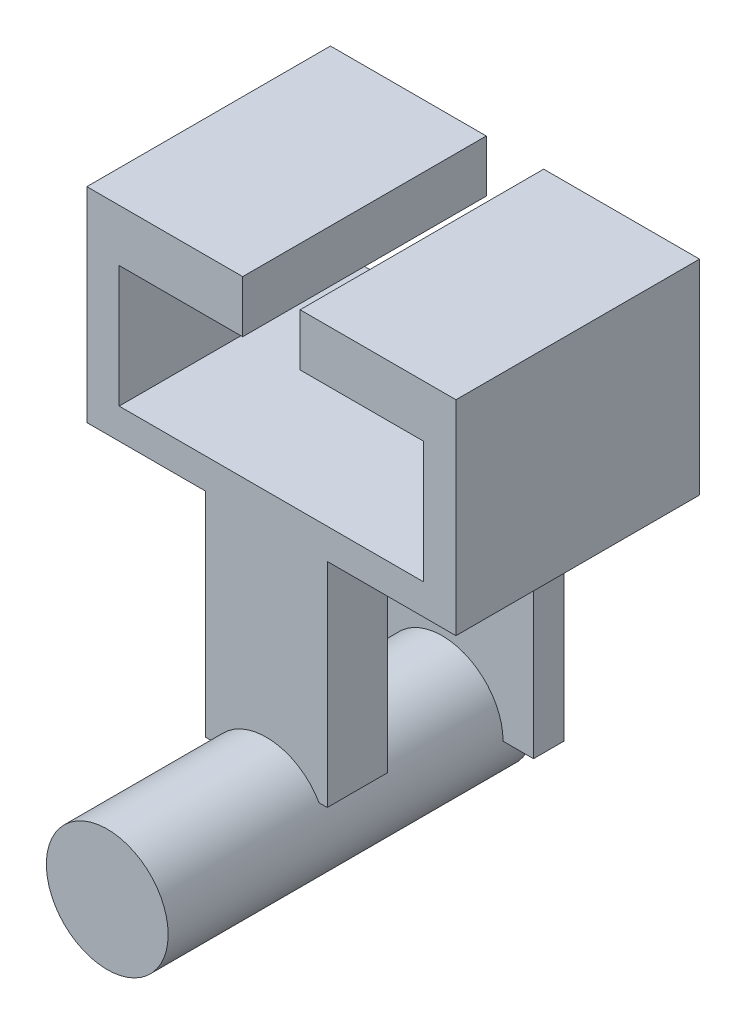
SolidWorks part; units mm, degrees
material "ASTM A36 Steel"
ref_plane "Front Plane" through (0, 0, 0) normal (0, 0, 1) x (1, 0, 0)
ref_plane "Top Plane" through (0, 0, 0) normal (0, 1, 0) x (1, 0, 0)
ref_plane "Right Plane" through (0, 0, 0) normal (1, 0, 0) x (0, 0, -1)
sketch "Sketch3" plane through (0, 0, 0) normal (0, 0, 1) x (1, 0, 0)
  circle A0 centre (0, 0) radius 12.7
  dimension "D1" = 25.4
extrude "Boss-Extrude1" add sketch "Sketch3" along normal blind 76.2
sketch "Sketch4" plane through (0, 0, 0) normal (0, 0, -1) x (-1, 0, 0)
  line L0 (0, 0) -> (19.05, 0)
  line L5 (19.05, 0) -> (19.05, 50.8)
  line L6 (19.05, 50.8) -> (-19.05, 50.8)
  line L7 (-19.05, 50.8) -> (-19.05, 0)
  line L8 (-19.05, 0) -> (0, 0)
  dimension "D1" = 50.8
  dimension "D2" = 38.1
extrude "Boss-Extrude2" add sketch "Sketch4" against normal blind 6.35 contours L7 L8 L0 L5 L6
sketch "Sketch6" plane through (0, 50.8, 0) normal (0, 1, 0) x (1, 0, 0)
  line L1 (-30.7019, 7.7865) -> (32.7981, 7.7865)
  line L2 (-30.7019, 7.7865) -> (-30.7019, -43.0135)
  line L3 (-30.7019, -43.0135) -> (32.7981, -43.0135)
  line L4 (32.7981, 7.7865) -> (32.7981, -43.0135)
  dimension "D1" = 63.5
  dimension "D2" = 50.8
extrude "Boss-Extrude3" add sketch "Sketch6" along normal blind 6.35
sketch "Sketch8" plane through (32.7981, 0, 0) normal (1, 0, 0) x (0, 0, -1)
  line L1 (-43.0135, 57.15) -> (7.7865, 57.15)
  line L2 (-43.0135, 57.15) -> (-43.0135, 50.8)
  line L3 (-43.0135, 50.8) -> (7.7865, 50.8)
  line L4 (7.7865, 57.15) -> (7.7865, 50.8)
sketch "Sketch9" plane through (32.7981, 0, 0) normal (1, 0, 0) x (0, 0, -1)
  line L1 (-43.0135, 57.15) -> (7.7865, 57.15)
  line L2 (-43.0135, 57.15) -> (-43.0135, 50.8)
  line L3 (-43.0135, 50.8) -> (7.7865, 50.8)
  line L4 (7.7865, 57.15) -> (7.7865, 50.8)
extrude "Boss-Extrude4" add sketch "Sketch9" along normal blind 0.3886
sketch "Sketch10" plane through (0, 57.15, 0) normal (0, 1, 0) x (1, 0, 0)
  line L0 (32.7981, -43.0135) -> (32.7981, 7.7865) construction
  line L1 (32.7981, 7.7865) -> (33.1867, 7.7865)
  line L2 (32.7981, 7.7865) -> (32.7981, -43.0135)
  line L3 (32.7981, -43.0135) -> (33.1867, -43.0135)
  line L4 (33.1867, 7.7865) -> (33.1867, -43.0135)
  line L5 (33.1867, 7.7865) -> (-30.7019, 7.7865) construction
extrude "Boss-Extrude5" add sketch "Sketch10" along normal blind 25.4
sketch "Sketch11" plane through (-30.7019, 0, 0) normal (-1, 0, 0) x (0, 0, 1)
  line L1 (-7.7865, 57.15) -> (43.0135, 57.15)
  line L2 (-7.7865, 57.15) -> (-7.7865, 50.8)
  line L3 (-7.7865, 50.8) -> (43.0135, 50.8)
  line L4 (43.0135, 57.15) -> (43.0135, 50.8)
extrude "Boss-Extrude6" add sketch "Sketch11" along normal blind 0.3886
sketch "Sketch13" plane through (0, 57.15, 0) normal (0, 1, 0) x (1, 0, 0)
  line L0 (-31.0906, -43.0135) -> (32.7981, -43.0135) construction
  line L1 (-31.0906, 7.7865) -> (-30.7019, 7.7865)
  line L2 (-31.0906, 7.7865) -> (-31.0906, -43.0135)
  line L3 (-31.0906, -43.0135) -> (-30.7019, -43.0135)
  line L4 (-30.7019, 7.7865) -> (-30.7019, -43.0135)
  dimension "D1" = 0.3886
extrude "Boss-Extrude7" add sketch "Sketch13" along normal blind 25.4
sketch "Sketch14" plane through (0, 82.55, 0) normal (0, 1, 0) x (1, 0, 0)
  line L1 (-31.0906, 7.7865) -> (-30.7019, 7.7865)
  line L2 (-31.0906, 7.7865) -> (-31.0906, -43.0135)
  line L3 (-31.0906, -43.0135) -> (-30.7019, -43.0135)
  line L4 (-30.7019, 7.7865) -> (-30.7019, -43.0135)
extrude "Boss-Extrude8" add sketch "Sketch14" along normal blind 10.8712
sketch "Sketch15" plane through (-30.7019, 0, 0) normal (1, 0, 0) x (0, 0, -1)
  line L0 (7.7865, 93.4212) -> (7.7865, 57.15) construction
  line L1 (-43.0135, 93.4212) -> (7.7865, 93.4212)
  line L2 (-43.0135, 93.4212) -> (-43.0135, 82.55)
  line L3 (-43.0135, 82.55) -> (7.7865, 82.55)
  line L4 (7.7865, 93.4212) -> (7.7865, 82.55)
  dimension "D1" = 10.8712
extrude "Boss-Extrude9" add sketch "Sketch15" along normal blind 25.7632
sketch "Sketch16" plane through (0, 82.55, 0) normal (0, 1, 0) x (1, 0, 0)
  line L1 (32.7981, 7.7865) -> (33.1867, 7.7865)
  line L2 (32.7981, 7.7865) -> (32.7981, -43.0135)
  line L3 (32.7981, -43.0135) -> (33.1867, -43.0135)
  line L4 (33.1867, 7.7865) -> (33.1867, -43.0135)
extrude "Boss-Extrude10" add sketch "Sketch16" along normal blind 10.8712
sketch "Sketch17" plane through (32.7981, 0, 0) normal (-1, 0, 0) x (0, 0, 1)
  line L0 (43.0135, 93.4212) -> (43.0135, 57.15) construction
  line L1 (-7.7865, 93.4212) -> (43.0135, 93.4212)
  line L2 (-7.7865, 93.4212) -> (-7.7865, 82.55)
  line L3 (-7.7865, 82.55) -> (43.0135, 82.55)
  line L4 (43.0135, 93.4212) -> (43.0135, 82.55)
  dimension "D1" = 10.8712
extrude "Boss-Extrude11" add sketch "Sketch17" along normal blind 25.7632
sketch "Sketch21" plane through (0, 0, 0) normal (1, 0, 0) x (0, 0, -1)
  line L0 (-6.35, 50.8) -> (-6.35, 0) construction
  line L1 (-6.35, 25.4) -> (-17.6135, 50.8)
  line L2 (-43.0135, 50.8) -> (7.7865, 50.8) construction
rib "Rib4" sketch "Sketch21" sketch "Sketch21" thickness 25.4 extrusion direction parallel to sketch draft on no parameters "D1"=25.4
sketch "Sketch22" plane through (0, 0, 0) normal (1, 0, 0) x (0, 0, -1)
  line L0 (0, 25.4) -> (7.7865, 50.8)
  line L1 (0, 50.8) -> (0, 0) construction
rib "Rib15" sketch "Sketch22" sketch "Sketch22" thickness 25.4 extrusion direction parallel to sketch draft on no parameters "D1"=25.4
sketch "Sketch26" plane through (0, 50.8, 0) normal (0, -1, 0) x (-1, 0, 0)
  line L0 (31.0906, -43.0135) -> (-33.1867, -43.0135) construction
  line L1 (12.7, -43.0135) -> (-12.7, -43.0135)
  line L2 (12.7, -43.0135) -> (12.7, -30.4132)
  line L3 (12.7, -30.4132) -> (-12.7, -30.4132)
  line L4 (-12.7, -43.0135) -> (-12.7, -30.4132)
  line L5 (12.7, -76.2) -> (12.7, -6.35) construction
  line L6 (-12.7, -6.35) -> (-12.7, -76.2) construction
extrude "Boss-Extrude12" add sketch "Sketch26" along normal blind 44.45 contours L2 L3 L4 L1
sketch "Sketch27" plane through (33.1867, 0, 0) normal (1, 0, 0) x (0, 0, -1)
  line L1 (-43.0135, 93.4212) -> (7.7865, 93.4212)
  line L2 (-43.0135, 93.4212) -> (-43.0135, 50.8)
  line L3 (-43.0135, 50.8) -> (7.7865, 50.8)
  line L4 (7.7865, 93.4212) -> (7.7865, 50.8)
extrude "Boss-Extrude13" add sketch "Sketch27" along normal blind 6.35
sketch "Sketch28" plane through (-31.0906, 0, 0) normal (-1, 0, 0) x (0, 0, 1)
  line L1 (-7.7865, 93.4212) -> (43.0135, 93.4212)
  line L2 (-7.7865, 93.4212) -> (-7.7865, 50.8)
  line L3 (-7.7865, 50.8) -> (43.0135, 50.8)
  line L4 (43.0135, 93.4212) -> (43.0135, 50.8)
extrude "Boss-Extrude14" add sketch "Sketch28" along normal blind 6.35
equation "\"Length_A\"= 3in"
equation "\"Diameter_A\"= 1in"
equation "\"Width_B\"= 1.5in"
equation "\"Length_B\"= 2in"
equation "\"Thickness_B\"= 0.25in"
equation "\"Length_C\"= 2.5in"
equation "\"Base_C\"= 2in"
equation "\"Height_C\"= 0.250in"
equation "\"Length_D\"= 2in"
equation "\"Base_D\"= 1.498in"
equation "\"Thickness_D\"=0.0153"
equation "\"Length_E\"= 2in"
equation "\"Base_E\"= 0.9990"
equation "\"Height_E\"= 0.428in"
equation "\"Sy\"= 36000"
equation "\"E\"= 29000000"
equation "\"deflection\"= 0.005in"
equation "\"D1@Sketch3\"=\"Diameter_A\""
equation "\"D1@Boss-Extrude1\"=\"Length_A\""
equation "\"D1@Sketch4\"=\"Length_B\""
equation "\"D1@Boss-Extrude2\"=\"Thickness_B\""
equation "\"D1@Sketch6\"=\"Length_C\""
equation "\"D2@Sketch6\"=\"Base_C\""
equation "\"D1@Boss-Extrude3\"=\"Height_C\""
equation "\"D1@Boss-Extrude4\"=\"Thickness_D\""
equation "\"D1@Boss-Extrude5\"=1in"
equation "\"D1@Boss-Extrude6\"=\"Thickness_D\""
equation "\"D1@Sketch13\"=\"Thickness_D\""
equation "\"D1@Boss-Extrude7\"=1in"
equation "\"D1@Boss-Extrude8\"=\"Height_E\""
equation "\"D1@Sketch15\"=\"Height_E\""
equation "\"D1@Boss-Extrude9\"=\"Base_E\"+\"Thickness_D\""
equation "\"D1@Boss-Extrude10\"=\"Height_E\""
equation "\"D1@Sketch17\"=\"Height_E\""
equation "\"D1@Boss-Extrude11\"=\"Thickness_D\"+\"Base_E\""
